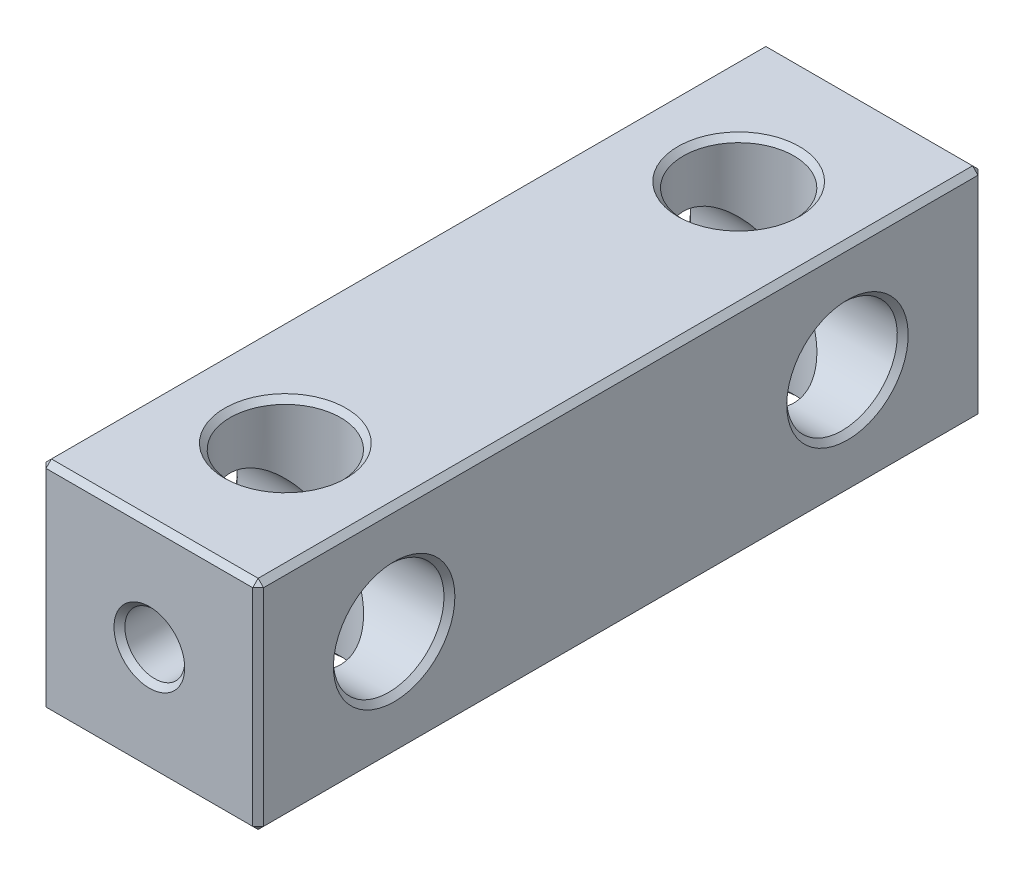
SolidWorks part; units mm, degrees
ref_plane "前视基准面" through (0, 0, 0) normal (0, 0, 1) x (1, 0, 0)
ref_plane "上视基准面" through (0, 0, 0) normal (0, 1, 0) x (1, 0, 0)
ref_plane "右视基准面" through (0, 0, 0) normal (1, 0, 0) x (0, 0, -1)
sketch "草图1" plane through (0, 0, 0) normal (0, 0, 1) x (1, 0, 0)
  line L1 (-6, 6) -> (6, 6)
  line L2 (-6, 6) -> (-6, -6)
  line L3 (-6, -6) -> (6, -6)
  line L4 (6, 6) -> (6, -6)
  line L5 (-6, 6) -> (6, -6) construction
  line L6 (-6, -6) -> (6, 6) construction
  point P0 (0, 0)
  dimension "D1" = 12
extrude "凸台-拉伸1" add sketch "草图1" along normal mid plane 40
hole_wizard "Ø6.1 (6.1) 直径孔1" positions "草图2" profile "草图3" hole size "Ø6.1" standard "GB" end condition through all
sketch "草图2" plane through (6, 0, 0) normal (1, 0, 0) x (0, 0, -1)
  line L0 (0, 0) -> (0, 50000) construction
  line L1 (-20, 6) -> (20, 6) construction
  line L2 (0, 0) -> (50000, 0) construction
  point P0 (-12.5, 0)
  point P2 (12.5, 0)
  point P10 (0, 6)
  dimension "D1" = 25
sketch "草图3" plane through (6, 0, 12.5) normal (0, 1, 0) x (0, 0, -1)
  line L0 (0, 0) -> (0, 12)
  line L1 (0, 12) -> (3.05, 12)
  line L2 (3.05, 12) -> (3.05, 0)
  line L5 (3.05, 0) -> (0, 0)
  line L11 (0, -6.35) -> (0, 107.95) construction
  dimension "通孔孔直径" = 6.1
  dimension "通孔孔深度" = 12
hole_wizard "Ø6.1 (6.1) 直径孔2" positions "草图4" profile "草图5" hole size "Ø6.1" standard "GB" end condition through all
sketch "草图4" plane through (0, 6, 0) normal (0, 1, 0) x (1, 0, 0)
  line L0 (0, 0) -> (0, 50000) construction
  line L1 (0, 0) -> (-50000, 0) construction
  point P0 (0, -12.5)
  point P2 (0, 12.5)
  dimension "D1" = 25
sketch "草图5" plane through (0, 6, 12.5) normal (1, 0, 0) x (0, 0, 1)
  line L0 (0, 0) -> (0, 12)
  line L1 (0, 12) -> (3.05, 12)
  line L2 (3.05, 12) -> (3.05, 0)
  line L5 (3.05, 0) -> (0, 0)
  line L11 (0, -6.35) -> (0, 107.95) construction
  dimension "通孔孔直径" = 6.1
  dimension "通孔孔深度" = 12
hole_wizard "M4 螺纹孔1" positions "草图6" profile "草图7" tap size "M4" standard "GB"
sketch "草图6" plane through (0, 0, 20) normal (0, 0, 1) x (1, 0, 0)
  point P0 (0, 0)
sketch "草图7" plane through (0, 0, 20) normal (1, 0, 0) x (0, -1, 0)
  line L0 (0, 0) -> (0, 4.45)
  line L1 (0, 4.45) -> (1.65, 4.45)
  line L2 (1.65, 4.45) -> (1.65, 0)
  line L5 (1.65, 0) -> (0, 0)
  line L11 (0, -6.35) -> (0, 107.95) construction
  dimension "通孔螺纹孔钻头直径" = 3.3
  dimension "通孔螺纹孔钻头深度" = 4.45
cosmetic thread "孔螺蚊线1"
hole_wizard "M4 螺纹孔2" positions "草图8" profile "草图9" tap size "M4" standard "GB"
sketch "草图8" plane through (0, 0, -20) normal (0, 0, -1) x (-1, 0, 0)
  point P0 (0, 0)
sketch "草图9" plane through (0, 0, -20) normal (1, 0, 0) x (0, 1, 0)
  line L0 (0, 0) -> (0, 4.45)
  line L1 (0, 4.45) -> (1.65, 4.45)
  line L2 (1.65, 4.45) -> (1.65, 0)
  line L5 (1.65, 0) -> (0, 0)
  line L11 (0, -6.35) -> (0, 107.95) construction
  dimension "通孔螺纹孔钻头直径" = 3.3
  dimension "通孔螺纹孔钻头深度" = 4.45
cosmetic thread "孔螺蚊线2"
chamfer "倒角1" distance 0.3 angle 45 22 edges at (-1.65, 0, -20) (1.65, 0, 20) (6, 0, -15.55) (6, 0, 9.45) (0, -6, -9.45) (0, -6, 15.55) (-6, 0, -15.55) (-6, 0, 9.45) (6, 0, 20) (6, 0, -20) (0, -6, 20) (6, -6, 0) (0, -6, -20) (-6, 0, 20) (-6, -6, 0) (-6, 0, -20) (6, 6, 0) (0, 6, 20) (-6, 6, 0) (0, 6, -20) (0, 6, -9.45) (0, 6, 15.55)
